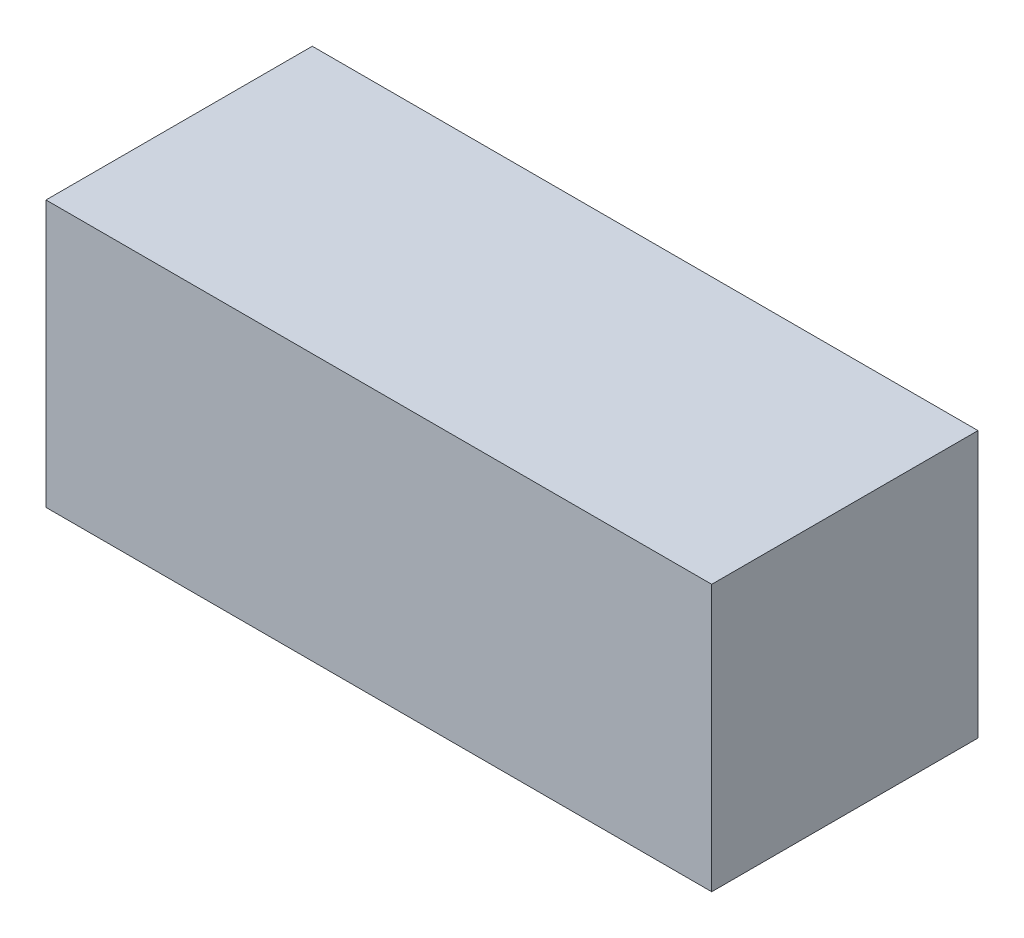
SolidWorks part; units mm, degrees
ref_plane "前基準面" through (0, 0, 0) normal (0, 0, 1) x (1, 0, 0)
ref_plane "上基準面" through (0, 0, 0) normal (0, 1, 0) x (1, 0, 0)
ref_plane "右基準面" through (0, 0, 0) normal (1, 0, 0) x (0, 0, -1)
sketch "草圖1" plane through (0, 0, 0) normal (0, 0, 1) x (1, 0, 0)
  line L1 (-25, 10) -> (25, 10)
  line L2 (-25, 10) -> (-25, -10)
  line L3 (-25, -10) -> (25, -10)
  line L4 (25, 10) -> (25, -10)
  line L5 (-25, 10) -> (25, -10) construction
  line L6 (-25, -10) -> (25, 10) construction
  point P0 (0, 0)
  dimension "D1" = 50
  dimension "D2" = 20
extrude "填料-伸長1" add sketch "草圖1" along normal mid plane 20
